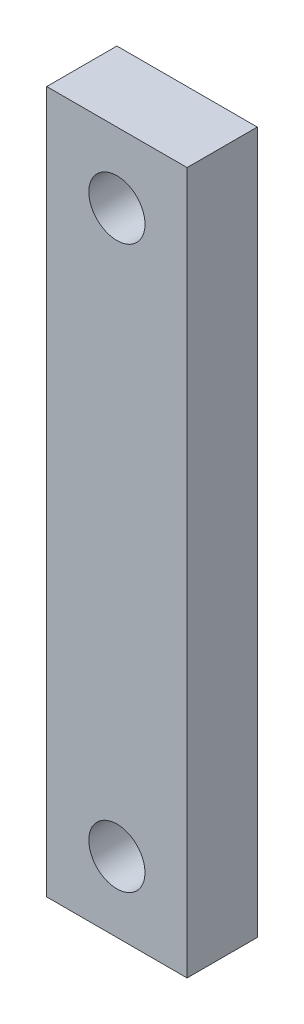
SolidWorks part; units mm, degrees
ref_plane "Front" through (0, 0, 0) normal (0, 0, 1) x (1, 0, 0)
ref_plane "Top" through (0, 0, 0) normal (0, 1, 0) x (1, 0, 0)
ref_plane "Right" through (0, 0, 0) normal (1, 0, 0) x (0, 0, -1)
sketch "Esquisse1" plane through (0, 0, 0) normal (0, 0, 1) x (1, 0, 0)
  line L1 (0, 0) -> (20, 0)
  line L2 (0, 0) -> (0, 100)
  line L3 (0, 100) -> (20, 100)
  line L4 (20, 0) -> (20, 100)
  dimension "D1" = 20
  dimension "D2" = 100
extrude "Boss.-Extru.1" add sketch "Esquisse1" along normal blind 10
sketch "Esquisse2" plane through (0, 0, 10) normal (0, 0, 1) x (1, 0, 0)
  line L0 (10, 0) -> (10, 100) construction
  line L1 (0, 0) -> (20, 0) construction
  line L2 (20, 100) -> (0, 100) construction
  line L3 (0, 50) -> (20, 50) construction
  line L4 (0, 100) -> (0, 0) construction
  line L5 (20, 0) -> (20, 100) construction
  circle A0 centre (10, 90) radius 4
  circle A1 centre (10, 10) radius 4
  dimension "D1" = 8
  dimension "D2" = 10
extrude "Enlèv. mat.-Extru.1" cut sketch "Esquisse2" against normal through all
